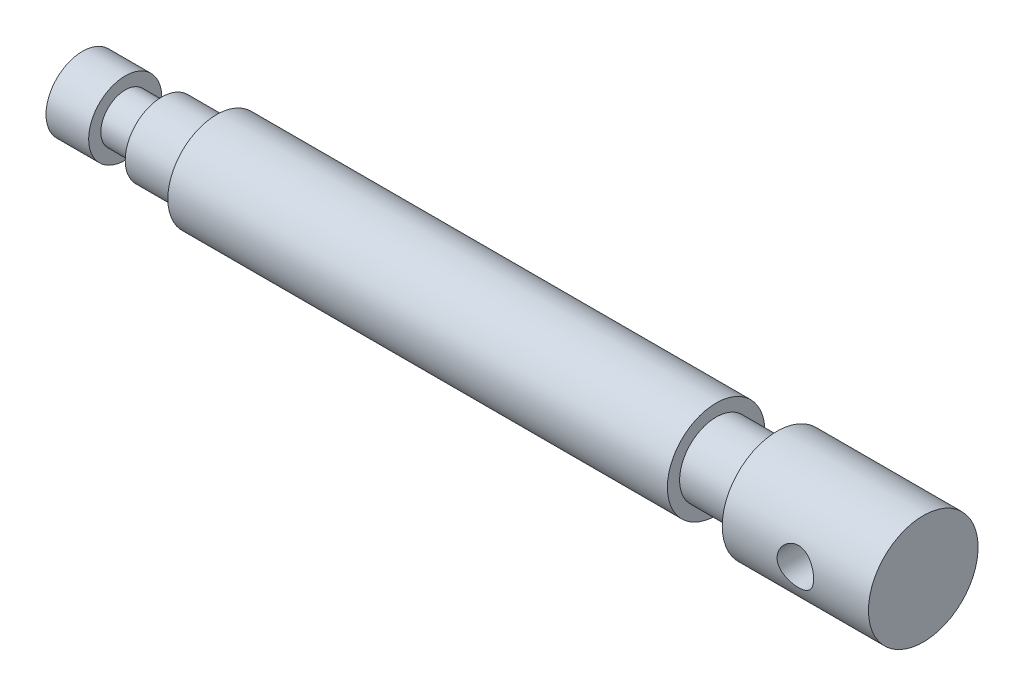
SolidWorks part; units mm, degrees
ref_plane "Front Plane" through (0, 0, 0) normal (0, 0, 1) x (1, 0, 0)
ref_plane "Top Plane" through (0, 0, 0) normal (0, 1, 0) x (1, 0, 0)
ref_plane "Right Plane" through (0, 0, 0) normal (1, 0, 0) x (0, 0, -1)
sketch "Sketch1" plane through (0, 0, 0) normal (0, 0, 1) x (1, 0, 0)
  line L0 (-164.2485, 0) -> (163.8565, 0) construction
  line L1 (-134.8484, 0) -> (-134.8484, 6)
  line L2 (-134.8484, 6) -> (-127.8484, 6)
  line L3 (-127.8484, 6) -> (-127.8484, 4)
  line L4 (-127.8484, 4) -> (-121.8484, 4)
  line L5 (-121.8484, 4) -> (-121.8484, 6)
  line L6 (-121.8484, 6) -> (-112.8484, 6)
  line L7 (-112.8484, 6) -> (-112.8484, 8)
  line L8 (-112.8484, 8) -> (-30.8484, 8)
  line L9 (-30.8484, 8) -> (-30.8484, 6)
  line L10 (-30.8484, 6) -> (-20.8484, 6)
  line L11 (-20.8484, 6) -> (-20.8484, 9)
  line L12 (-20.8484, 9) -> (3.1516, 9)
  line L13 (3.1516, 9) -> (3.1516, 0)
  line L14 (-134.8484, 0) -> (3.1516, 0)
  line L15 (3.1516, 0) -> (2.6441, -0.141)
  dimension "D1" = 6
  dimension "D2" = 7
  dimension "D3" = 2
  dimension "D4" = 6
  dimension "D5" = 2
  dimension "D6" = 9
  dimension "D7" = 2
  dimension "D8" = 82
  dimension "D9" = 2
  dimension "D10" = 10
  dimension "D11" = 3
  dimension "D12" = 24
revolve "Revolve1" add sketch "Sketch1" angle 360 about L0
sketch "Sketch2" plane through (0, 0, 0) normal (0, 0, 1) x (1, 0, 0)
  line L0 (3.1516, -9) -> (3.1516, 9) construction
  line L1 (3.1516, 9) -> (-20.8484, 9) construction
  circle A0 centre (-8.8484, 0) radius 3
  dimension "D3" = 6
  dimension "D1" = 12
  dimension "D2" = 9
extrude "Cut-Extrude1" cut sketch "Sketch2" along normal blind 20 and the other way blind 20
